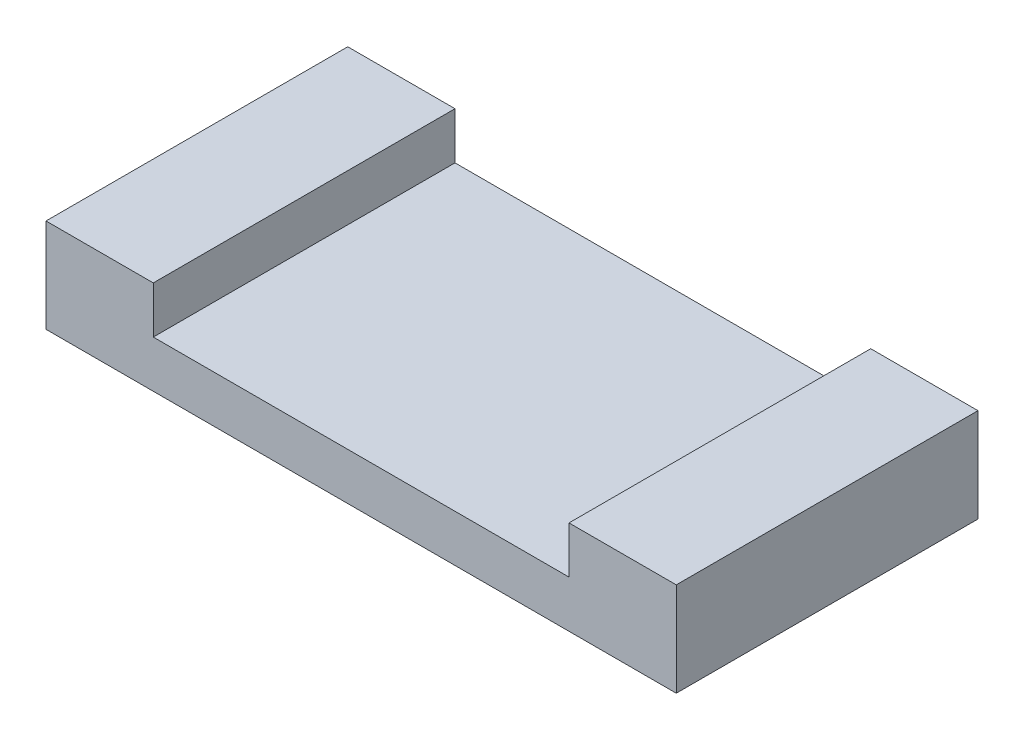
SolidWorks part; units mm, degrees
ref_plane "Front" through (0, 0, 0) normal (0, 0, 1) x (1, 0, 0)
ref_plane "Top" through (0, 0, 0) normal (0, 1, 0) x (1, 0, 0)
ref_plane "Right" through (0, 0, 0) normal (1, 0, 0) x (0, 0, -1)
sketch "Sketch1" plane through (0, 0, 0) normal (0, 1, 0) x (1, 0, 0)
  line L1 (23.5, 11.25) -> (-23.5, 11.25)
  line L2 (23.5, 11.25) -> (23.5, -11.25)
  line L3 (23.5, -11.25) -> (-23.5, -11.25)
  line L4 (-23.5, 11.25) -> (-23.5, -11.25)
  line L5 (0, -11.25) -> (0, 11.25) construction
  line L6 (23.5, 0) -> (-23.5, 0) construction
  point P0 (0, 0)
  dimension "D1" = 47
  dimension "D2" = 22.5
extrude "Boss-Extrude1" add sketch "Sketch1" against normal blind 2
sketch "Sketch2" plane through (0, 0, 11.25) normal (0, 0, 1) x (1, 0, 0)
  line L0 (-23.5, 0) -> (23.5, 0) construction
  line L1 (-23.5, 0) -> (23.5, 0)
  line L2 (-23.5, 0) -> (-23.5, 5)
  line L3 (-23.5, 5) -> (-15.5, 5)
  line L4 (-15.5, 5) -> (-15.5, 1.5017)
  line L5 (-15.5, 1.5017) -> (15.5, 1.5017)
  line L6 (15.5, 1.5017) -> (15.5, 5)
  line L7 (15.5, 5) -> (23.5, 5)
  line L8 (23.5, 5) -> (23.5, 0)
  point P2 (0, 1.5017)
  dimension "D1" = 5
  dimension "D2" = 8
extrude "Boss-Extrude2" add sketch "Sketch2" against normal up to surface (22.5 mm away) up to face at (0, -1, -11.25)
